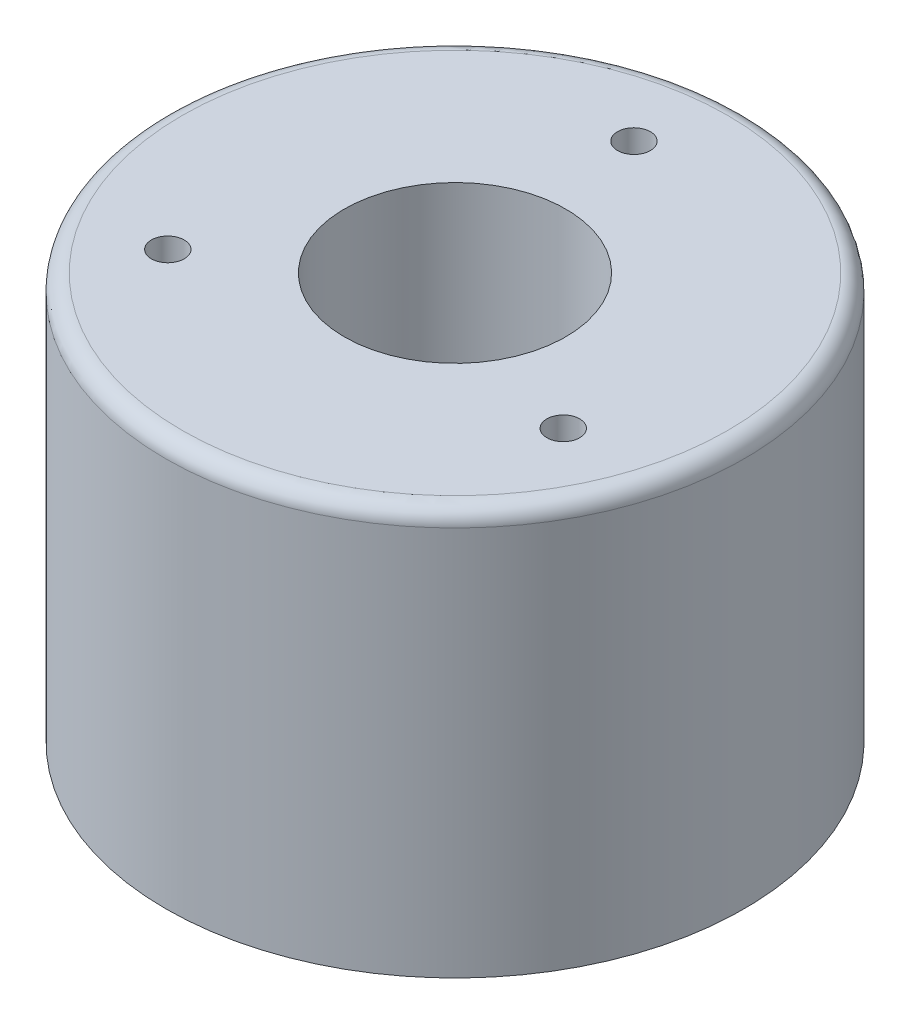
SolidWorks part; units mm, degrees
ref_plane "Front Plane" through (0, 0, 0) normal (0, 0, 1) x (1, 0, 0)
ref_plane "Top Plane" through (0, 0, 0) normal (0, 1, 0) x (1, 0, 0)
ref_plane "Right Plane" through (0, 0, 0) normal (1, 0, 0) x (0, 0, -1)
sketch "Sketch1" plane through (0, 0, 0) normal (0, 1, 0) x (1, 0, 0)
  line L0 (0, 0) -> (23.366, -9.9595) construction
  line L1 (0, 0) -> (-20.3082, -15.2558) construction
  line L2 (0, 0) -> (-3.0578, 25.2153) construction
  line L3 (-20.3082, -15.2558) -> (-18.4389, -16.0525) construction
  line L4 (3.0578, -25.2153) -> (5.0886, -23.6897) construction
  line L6 (21.7413, -11.18) -> (23.366, -9.9595) construction
  circle A0 centre (0, 0) radius 35.814
  circle A1 centre (-20.3082, -15.2558) radius 2.032
  circle A2 centre (-3.0578, 25.2153) radius 2.032
  circle A3 centre (23.366, -9.9595) radius 2.032
  dimension "D1" = 4.064
  dimension "D2" = 4.064
  dimension "D3" = 4.064
  dimension "D11" = 71.628
  dimension "D4" = 120
  dimension "D5" = 120
  dimension "D6" = 25.4
  dimension "D7" = 25.4
  dimension "D8" = 25.4
  dimension "D9" = 25.4
  dimension "D10" = 25.4
extrude "Boss-Extrude1" add sketch "Sketch1" along normal blind 50.292
sketch "Sketch2" plane through (0, 50.292, 0) normal (0, 1, 0) x (1, 0, 0)
  circle A0 centre (0, 0) radius 13.716
extrude "Cut-Extrude1" cut sketch "Sketch2" against normal blind 31.75
fillet "Fillet1" radius 2.032 1 edges at (0, 50.292, 35.814)
